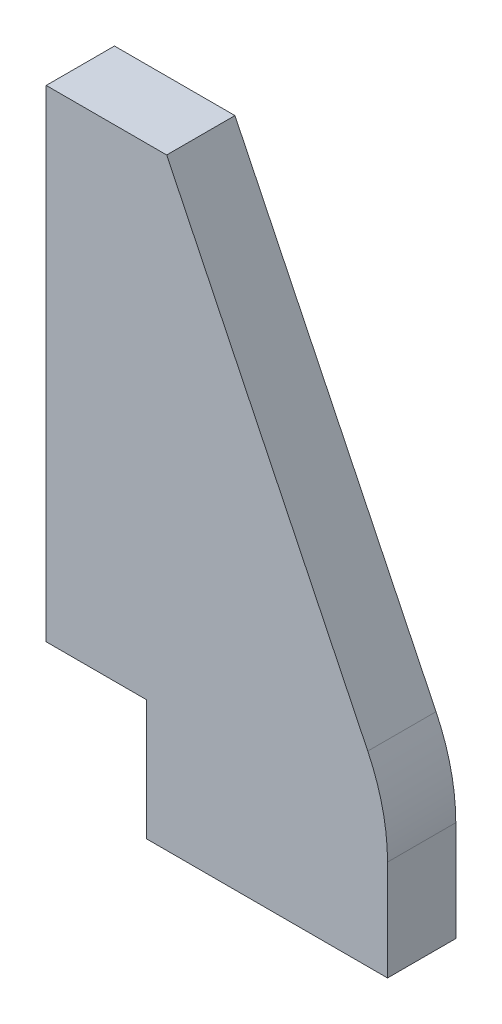
SolidWorks part; units mm, degrees
ref_plane "Piano frontale" through (0, 0, 0) normal (0, 0, 1) x (1, 0, 0)
ref_plane "Piano superiore" through (0, 0, 0) normal (0, 1, 0) x (1, 0, 0)
ref_plane "Piano destro" through (0, 0, 0) normal (1, 0, 0) x (0, 0, -1)
sketch "Schizzo1" plane through (0, 0, 0) normal (0, 0, 1) x (1, 0, 0)
  line L0 (0, 0) -> (85, 0)
  line L1 (85, 0) -> (85, 25)
  line L2 (0, 0) -> (0, 150)
  line L3 (0, 150) -> (30, 150)
  line L4 (30, 150) -> (80.0784, 46.4763)
  arc A1 (80.0784, 46.4763) -> (85, 25) centre (35.6818, 25) cw
  dimension "D1" = 85
  dimension "D2" = 150
  dimension "D3" = 30
  dimension "D4" = 115
  dimension "D5" = 25
extrude "Estrusione-Estrusione1" add sketch "Schizzo1" along normal blind 17
sketch "Schizzo2" plane through (0, 0, 0) normal (0, 0, -1) x (-1, 0, 0)
  line L1 (0, 0) -> (-25, 0)
  line L2 (0, 0) -> (0, 30)
  line L3 (0, 30) -> (-25, 30)
  line L4 (-25, 0) -> (-25, 30)
  dimension "D1" = 25
  dimension "D2" = 30
extrude "Taglio-Estrusione1" cut sketch "Schizzo2" against normal blind 17
